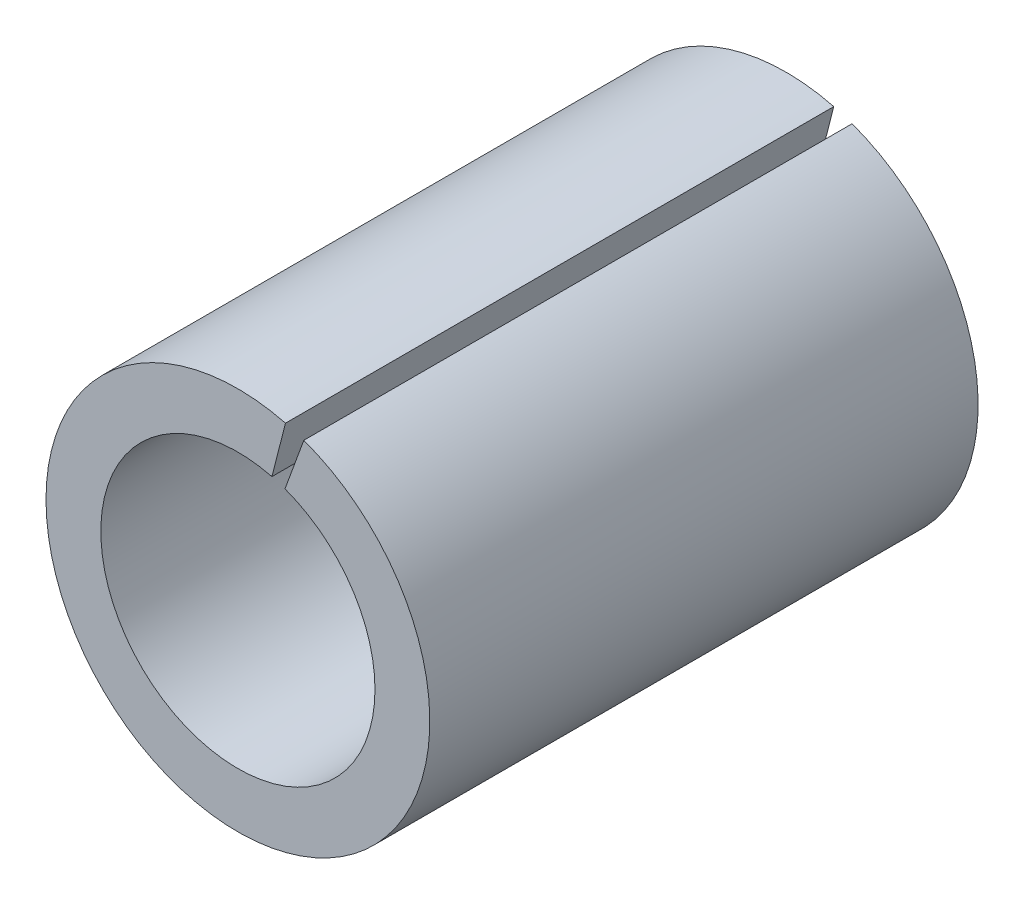
SolidWorks part; units mm, degrees
ref_plane "前视基准面" through (0, 0, 0) normal (0, 0, 1) x (1, 0, 0)
ref_plane "上视基准面" through (0, 0, 0) normal (0, 1, 0) x (1, 0, 0)
ref_plane "右视基准面" through (0, 0, 0) normal (1, 0, 0) x (0, 0, -1)
sketch "草图1" plane through (0, 0, 0) normal (0, 0, 1) x (1, 0, 0)
  circle A0 centre (0, 0) radius 3.5
  circle A1 centre (0, 0) radius 2.5
  dimension "D1" = 5
  dimension "D2" = 7
extrude "凸台-拉伸1" add sketch "草图1" along normal blind 10
sketch "草图2" plane through (0, 0, 10) normal (0, 0, 1) x (1, 0, 0)
  line L0 (0, 0) -> (1.1956, 4.6702)
  line L1 (1.1956, 4.6702) -> (1.7082, 4.6702)
  line L2 (1.7082, 4.6702) -> (0, 0)
extrude "切除-拉伸1" cut sketch "草图2" against normal blind 100
